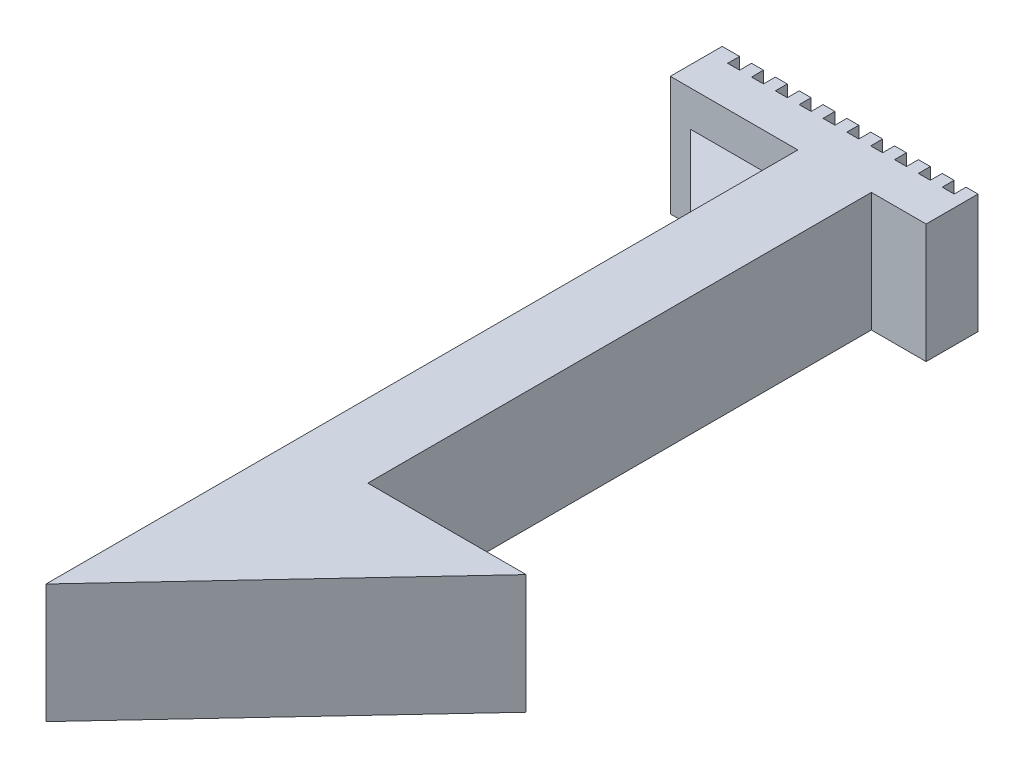
SolidWorks part; units mm, degrees
ref_plane "Front" through (0, 0, 0) normal (0, 0, 1) x (1, 0, 0)
ref_plane "Top" through (0, 0, 0) normal (0, 1, 0) x (1, 0, 0)
ref_plane "Right" through (0, 0, 0) normal (1, 0, 0) x (0, 0, -1)
sketch "Эскиз1" plane through (0, 0, 0) normal (0, 1, 0) x (1, 0, 0)
  line L0 (0, 0) -> (19.459, 20.8264)
  line L1 (19.459, 20.8264) -> (6.1689, 20.8264)
  line L2 (6.1689, 20.8264) -> (6.1689, 63.0732)
  line L3 (0, 0) -> (0, 63.0732)
  line L4 (0, 63.0732) -> (-10.6971, 63.0732)
  line L5 (-10.6971, 63.0732) -> (-10.6971, 67.4251)
  line L6 (-10.6971, 67.4251) -> (10.7622, 67.4251)
  line L7 (10.7622, 67.4251) -> (10.7622, 63.0732)
  line L8 (10.7622, 63.0732) -> (6.1689, 63.0732)
extrude "Бобышка-Вытянуть1" add sketch "Эскиз1" along normal blind 10
ref_plane "Плоскость1" through (0, 5, 0) normal (0, -1, 0) x (-1, 0, 0)
sketch "Эскиз3" plane through (0, 5, 0) normal (0, -1, 0) x (-1, 0, 0)
  line L0 (9, 63.0732) -> (0, 54.0732)
  line L1 (10.6971, 63.0732) -> (0, 63.0732) construction
  line L2 (0, 63.0732) -> (0, 0) construction
  line L3 (0, 54.0732) -> (0, 63.0732)
  line L4 (0, 63.0732) -> (9, 63.0732)
  dimension "D1" = 9
extrude "Бобышка-Вытянуть2" add sketch "Эскиз3" along normal blind 2 and the other way blind 2
sketch "Эскиз4" plane through (0, 0, -67.4251) normal (0, 0, -1) x (-1, 0, 0)
  line L0 (-10.7622, 10) -> (10.6971, 10) construction
  line L1 (-9.7622, 10) -> (-8.7622, 10)
  line L2 (-9.7622, 10) -> (-9.7622, 0)
  line L3 (-9.7622, 0) -> (-8.7622, 0)
  line L4 (-8.7622, 10) -> (-8.7622, 0)
  line L5 (-10.7622, 0) -> (10.6971, 0) construction
  line L6 (-10.7622, 10) -> (-10.7622, 0) construction
  dimension "D1" = 1
  dimension "D2" = 1
extrude "Вырез-Вытянуть2" cut sketch "Эскиз4" against normal blind 1
pattern_linear "Линейный массив2" count 10 spacing 2 along (-1, 0, 0) of "Вырез-Вытянуть2"
